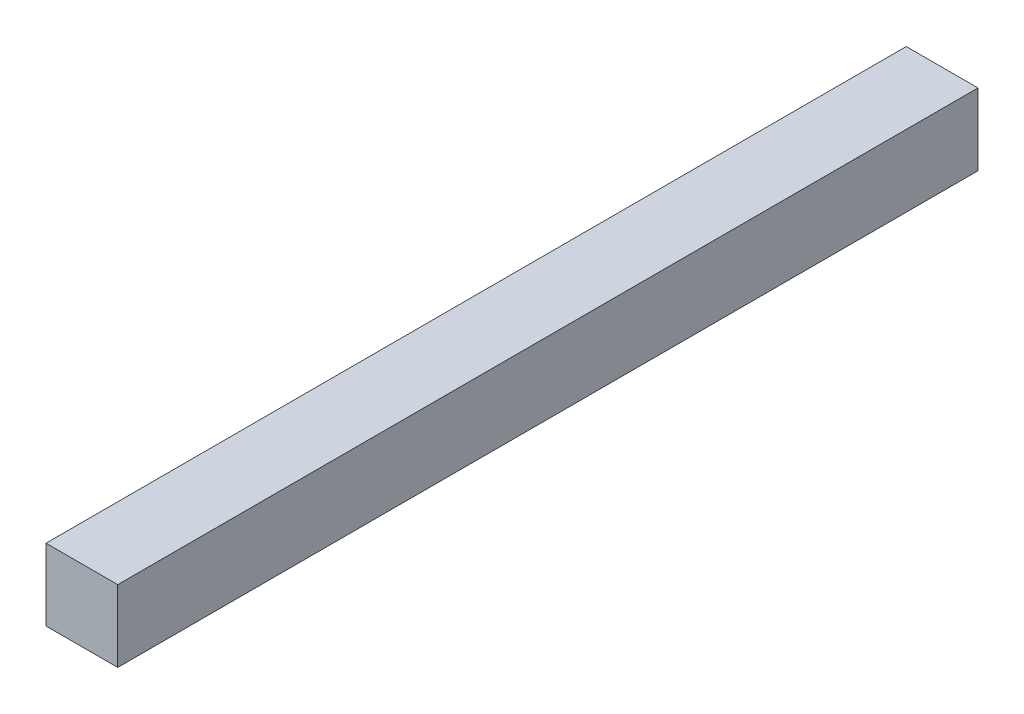
SolidWorks part; units mm, degrees
ref_plane "Front Plane" through (0, 0, 0) normal (0, 0, 1) x (1, 0, 0)
ref_plane "Top Plane" through (0, 0, 0) normal (0, 1, 0) x (1, 0, 0)
ref_plane "Right Plane" through (0, 0, 0) normal (1, 0, 0) x (0, 0, -1)
sketch "Sketch1" plane through (0, 0, 0) normal (0, 0, 1) x (1, 0, 0)
  line L1 (0, 0) -> (3.175, 0)
  line L2 (0, 0) -> (0, 3.175)
  line L3 (0, 3.175) -> (3.175, 3.175)
  line L4 (3.175, 0) -> (3.175, 3.175)
  dimension "D1" = 3.175
  dimension "D2" = 3.175
extrude "Boss-Extrude1" add sketch "Sketch1" along normal blind 38.0746
